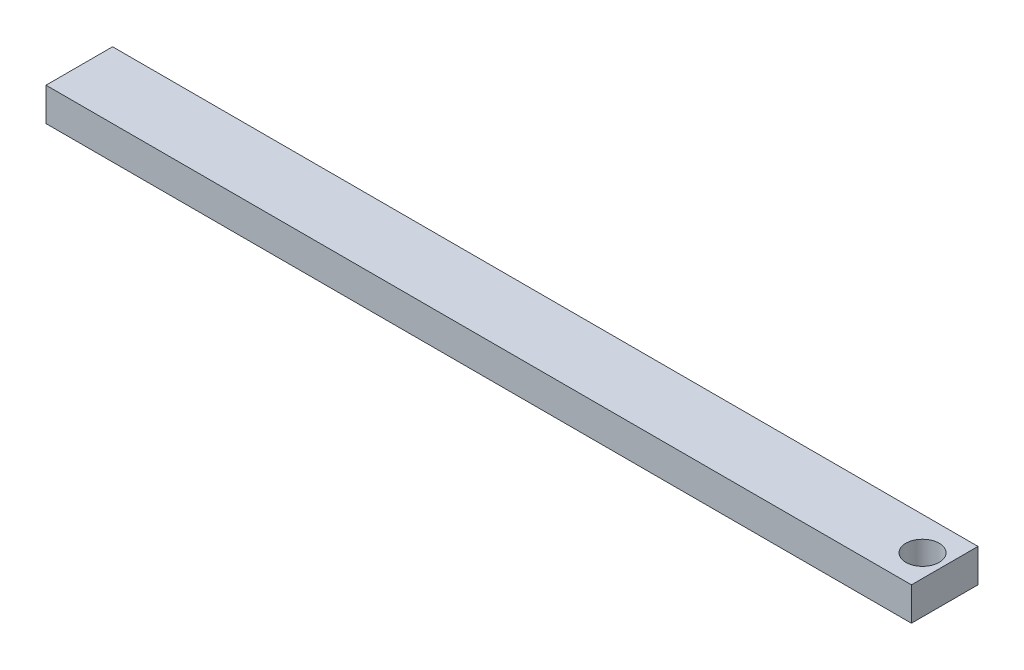
SolidWorks part; units mm, degrees
ref_plane "Plan1" through (0, 0, 0) normal (0, 0, 1) x (1, 0, 0)
ref_plane "Plan2" through (0, 0, 0) normal (0, 1, 0) x (1, 0, 0)
ref_plane "Plan3" through (0, 0, 0) normal (1, 0, 0) x (0, 0, -1)
sketch "Esquisse1" plane through (0, 0, 0) normal (0, 0, 1) x (1, 0, 0)
  line L1 (80, -360) -> (-700, -360)
  line L2 (80, -360) -> (80, -390)
  line L3 (80, -390) -> (-700, -390)
  line L4 (-700, -360) -> (-700, -390)
extrude "Base-Extrusion" add sketch "Esquisse1" along normal mid plane 60
sketch "Esquisse3" plane through (0, -360, 0) normal (0, 1, 0) x (-1, 0, 0)
  line L0 (-100, 0) -> (110, 0) construction
  line L3 (-80, 30) -> (-80, -30) construction
  circle A0 centre (-60, 0) radius 15
  dimension "D2" = 30
  dimension "D1" = 20
extrude "Enlèv. mat.-Extru.1" cut sketch "Esquisse3" against normal through all
ref_plane "Plan axe roue" through (0, -35, 0) normal (0, 1, 0) x (-1, 0, 0)
